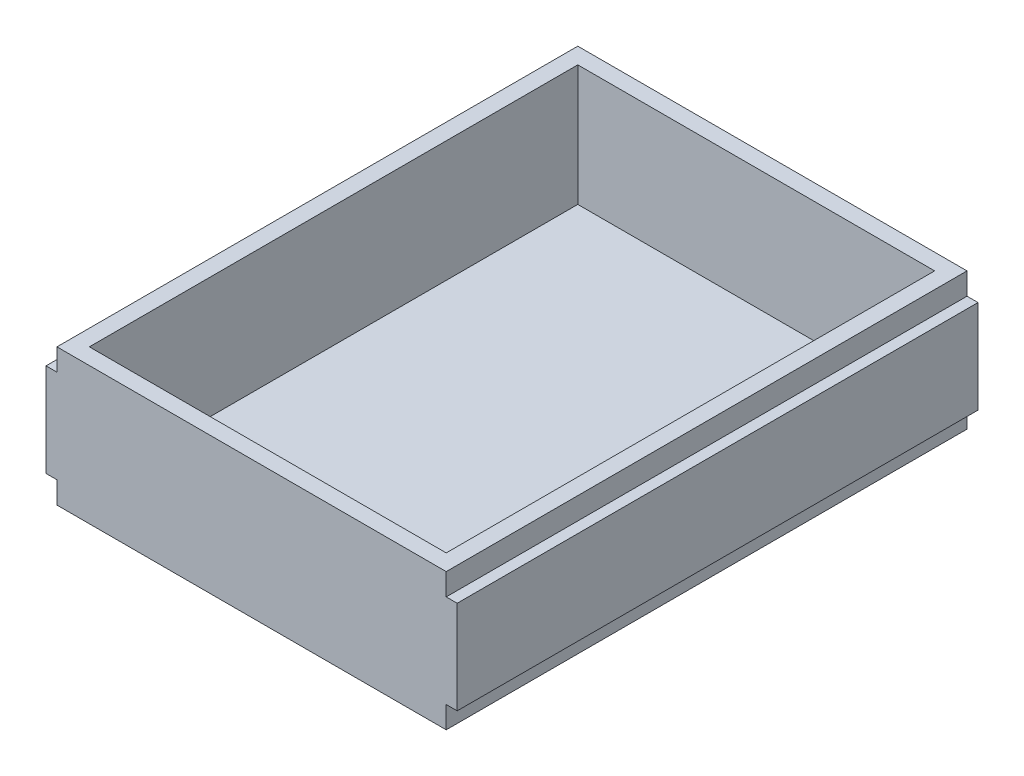
SolidWorks part; units mm, degrees
ref_plane "Alzado" through (0, 0, 0) normal (0, 0, 1) x (1, 0, 0)
ref_plane "Planta" through (0, 0, 0) normal (0, 1, 0) x (1, 0, 0)
ref_plane "Vista lateral" through (0, 0, 0) normal (1, 0, 0) x (0, 0, -1)
sketch "Croquis1" plane through (0, 0, 0) normal (0, 0, 1) x (1, 0, 0)
  line L1 (0, 0) -> (-72.136, 0)
  line L2 (0, 0) -> (0, 25.4)
  line L3 (0, 25.4) -> (-72.136, 25.4)
  line L4 (-72.136, 0) -> (-72.136, 25.4)
  dimension "D1" = 72.136
  dimension "D2" = 25.4
extrude "Saliente-Extruir1" add sketch "Croquis1" along normal blind 96.52
sketch "Croquis2" plane through (0, 0, 0) normal (0, 0, -1) x (-1, 0, 0)
  line L0 (0, 21.336) -> (-2.032, 21.336)
  line L1 (0, 0) -> (0, 25.4) construction
  line L2 (-2.032, 21.336) -> (-2.032, 4.064)
  line L3 (-2.032, 4.064) -> (0, 4.064)
  line L4 (0, 4.064) -> (0, 21.336)
  line L5 (36.068, 25.4) -> (36.068, 0) construction
  line L6 (0, 25.4) -> (72.136, 25.4) construction
  line L7 (72.136, 0) -> (0, 0) construction
  line L8 (74.168, 4.064) -> (72.136, 4.064)
  line L9 (74.168, 21.336) -> (74.168, 4.064)
  line L10 (72.136, 21.336) -> (74.168, 21.336)
  line L11 (72.136, 4.064) -> (72.136, 21.336)
  dimension "D1" = 2.032
  dimension "D2" = 4.064
  dimension "D3" = 4.064
shell "Vaciado1" thickness 3
extrude "Saliente-Extruir3" add sketch "Croquis2" against normal blind 96.52
sketch "Croquis4" plane through (0, 0, 0) normal (0, 0, -1) x (-1, 0, 0)
  line L0 (36.068, 25.4) -> (36.068, 0) construction
  line L1 (0, 25.4) -> (72.136, 25.4) construction
  line L2 (72.136, 0) -> (0, 0) construction
  line L4 (44.318, 1.2626) -> (27.818, 1.2626)
  line L5 (44.318, 1.2626) -> (44.318, 5.2626)
  line L6 (44.318, 5.2626) -> (27.818, 5.2626)
  line L7 (27.818, 1.2626) -> (27.818, 5.2626)
  line L8 (44.318, 1.2626) -> (27.818, 5.2626) construction
  line L9 (44.318, 5.2626) -> (27.818, 1.2626) construction
  point P6 (36.068, 3.2626)
  dimension "D1" = 16.5
  dimension "D2" = 4
extrude "Saliente-Extruir4" add sketch "Croquis4" along normal blind 4.5
